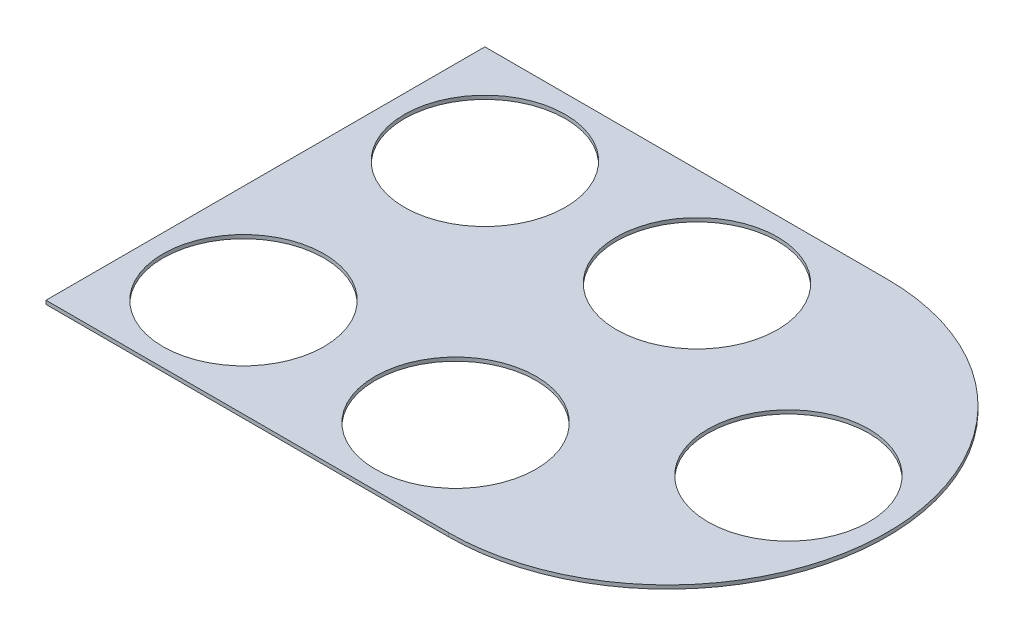
SolidWorks part; units mm, degrees
ref_plane "Front Plane" through (0, 0, 0) normal (0, 0, 1) x (1, 0, 0)
ref_plane "Top Plane" through (0, 0, 0) normal (0, 1, 0) x (1, 0, 0)
ref_plane "Right Plane" through (0, 0, 0) normal (1, 0, 0) x (0, 0, -1)
sketch "Sketch1" plane through (0, 0, 0) normal (0, 1, 0) x (1, 0, 0)
  line L0 (0, 152.4) -> (431.8, 152.4) construction
  line L1 (0, 0) -> (279.4, 0)
  line L2 (0, 0) -> (0, 304.8)
  line L3 (0, 304.8) -> (279.4, 304.8)
  line L4 (215.9, 0) -> (215.9, 330.2) construction
  circle A0 centre (68.58, 236.22) radius 55.88
  circle A1 centre (215.9, 236.22) radius 55.88
  circle A2 centre (363.22, 152.4) radius 55.88
  circle A3 centre (68.58, 68.58) radius 55.88
  circle A4 centre (215.9, 68.58) radius 55.88
  arc A5 (279.4, 0) -> (279.4, 304.8) centre (279.4, 152.4) ccw
  dimension "D3" = 111.76
  dimension "D6" = 215.9
  dimension "D7" = 12.7
  dimension "D4" = 12.7
  dimension "D5" = 12.7
  dimension "D1" = 304.8
  dimension "D2" = 431.8
extrude "Boss-Extrude1" add sketch "Sketch1" along normal blind 2.54
